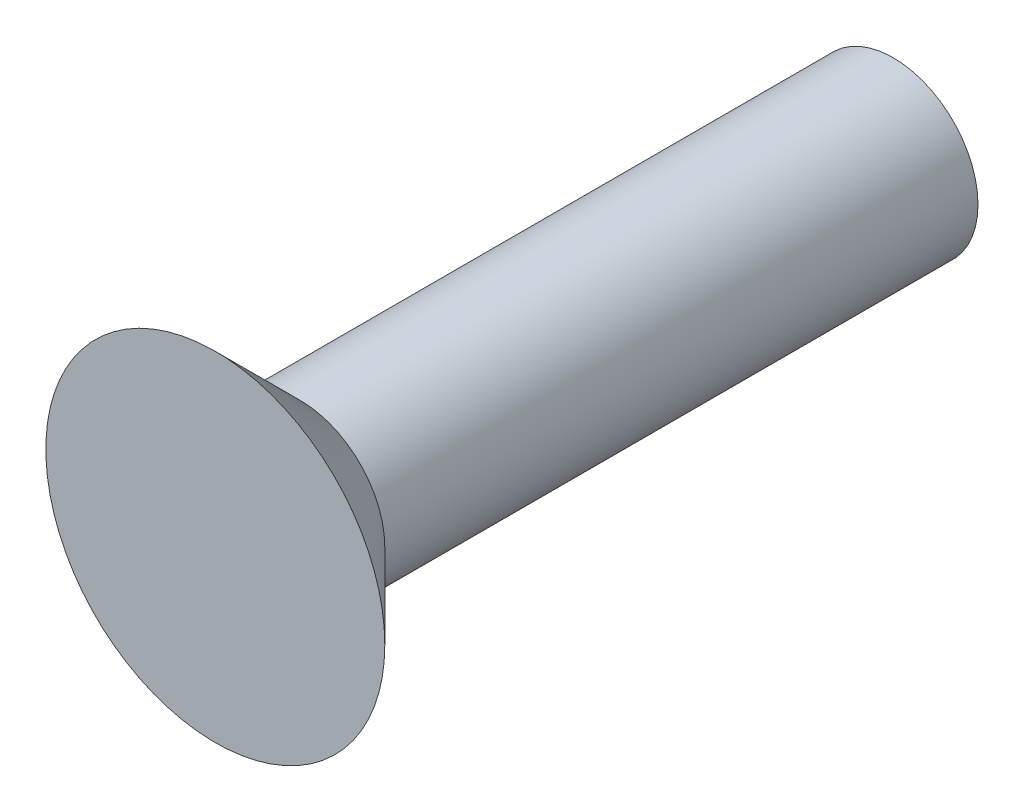
SolidWorks part; units mm, degrees
ref_plane "Front Plane" through (0, 0, 0) normal (0, 0, 1) x (1, 0, 0)
ref_plane "Top Plane" through (0, 0, 0) normal (0, 1, 0) x (1, 0, 0)
ref_plane "Right Plane" through (0, 0, 0) normal (1, 0, 0) x (0, 0, -1)
sketch "Sketch1" plane through (0, 0, 0) normal (0, 0, 1) x (1, 0, 0)
  circle A0 centre (0, 0) radius 2.5
extrude "Head_D5_90deg" add sketch "Sketch1" against normal blind 1.25 draft 45
sketch "Sketch2" plane through (0, 0, 0) normal (0, 0, 1) x (1, 0, 0)
  circle A0 centre (0, 0) radius 1.25
extrude "M2p5x0p45_Thread_Envelope" add sketch "Sketch2" along normal blind 8.75 from offset 10
